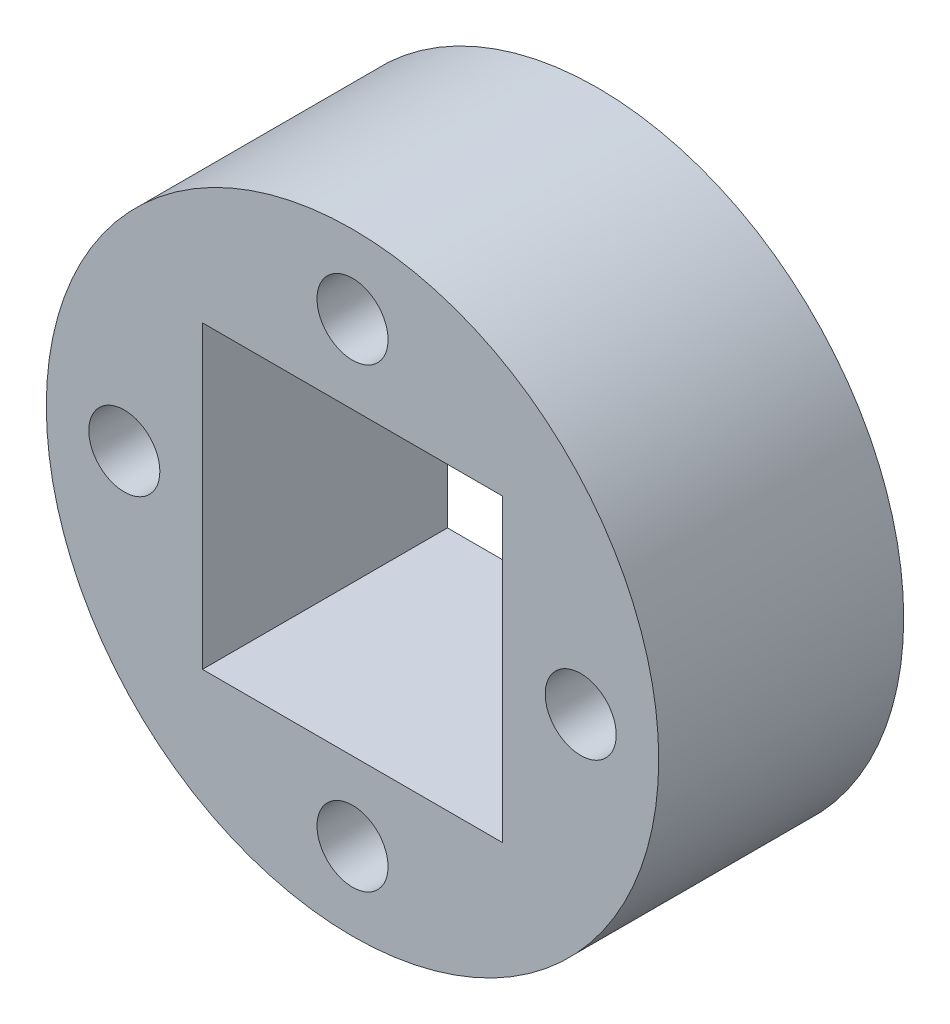
SolidWorks part; units mm, degrees
ref_plane "Front Plane" through (0, 0, 0) normal (0, 0, 1) x (1, 0, 0)
ref_plane "Top Plane" through (0, 0, 0) normal (0, 1, 0) x (1, 0, 0)
ref_plane "Right Plane" through (0, 0, 0) normal (1, 0, 0) x (0, 0, -1)
sketch "Sketch1" plane through (0, 0, 0) normal (0, 0, 1) x (1, 0, 0)
  circle A0 centre (0, 0) radius 12.5
  dimension "D2" = 25
extrude "Boss-Extrude1" add sketch "Sketch1" along normal mid plane 10
sketch "Sketch8" plane through (0, 0, 5) normal (0, 0, 1) x (1, 0, 0)
  line L2 (-6.125, 6.125) -> (6.125, 6.125)
  line L3 (-6.125, 6.125) -> (-6.125, -6.125)
  line L4 (-6.125, -6.125) -> (6.125, -6.125)
  line L5 (6.125, 6.125) -> (6.125, -6.125)
  line L6 (-6.125, 6.125) -> (6.125, -6.125) construction
  line L7 (-6.125, -6.125) -> (6.125, 6.125) construction
  point P5 (0, 0)
  point P14 (0, 0)
  dimension "D1" = 12.25
extrude "Cut-Extrude1" cut sketch "Sketch8" against normal up to next
sketch "Sketch11" plane through (0, 0, 5) normal (0, 0, 1) x (1, 0, 0)
  line L0 (6.125, -6.125) -> (6.125, 6.125) construction
  circle A0 centre (9.315, 0) radius 1.45
  circle A1 centre (0, -9.315) radius 1.45
  circle A2 centre (-9.315, 0) radius 1.45
  circle A3 centre (0, 9.315) radius 1.45
  point P13 (0, 0)
  dimension "D1" = 2.9
  dimension "D2" = 3.19
  dimension "D3" = 4
extrude "Cut-Extrude4" cut sketch "Sketch11" against normal up to next
equation "\"drumDiameter\"= 25"
equation "\"drumLength\"=10"
equation "\"foamThickness\"= 5"
equation "\"drumAbove\"= 0.6"
equation "\"holderThicc\"= 2"
equation "\"D1@Boss-Extrude1\"=\"drumLength\""
equation "\"squareBarLength\"= 12.25"
equation "\"D1@Sketch8\"=\"squareBarLength\""
equation "\"toothlen\"= 2.5"
